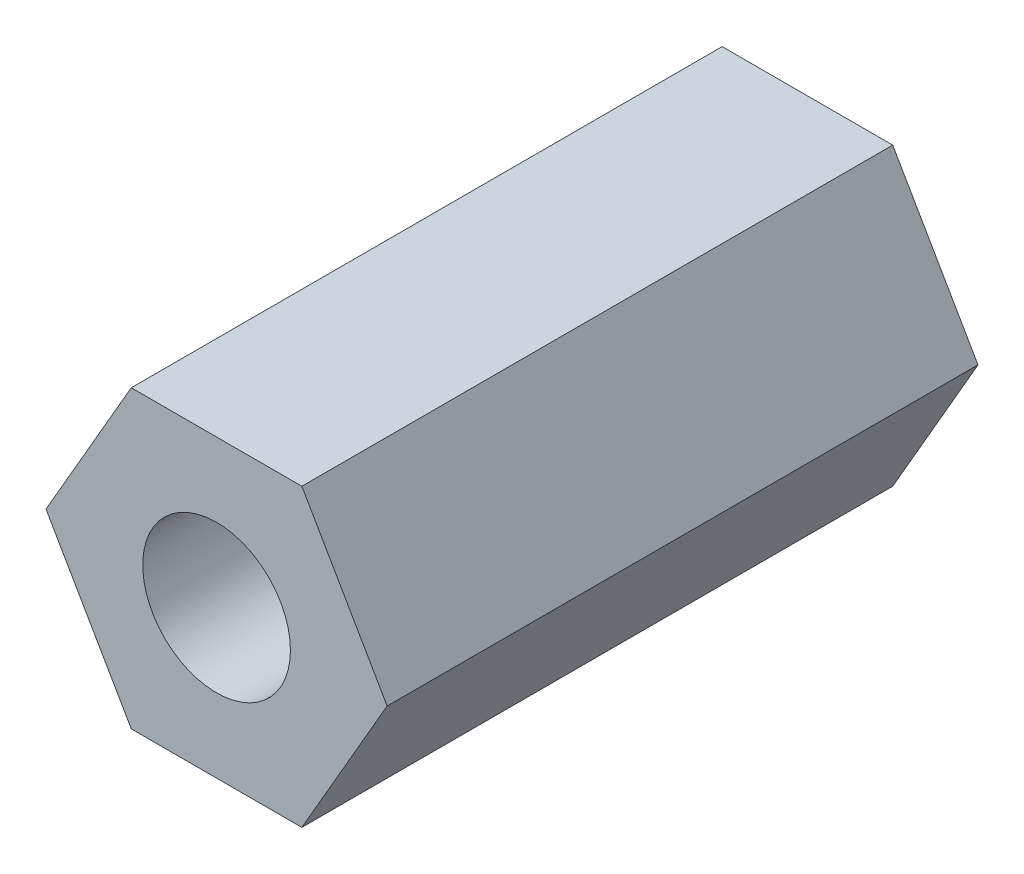
SolidWorks part; units mm, degrees
ref_plane "Front Plane" through (0, 0, 0) normal (0, 0, 1) x (1, 0, 0)
ref_plane "Top Plane" through (0, 0, 0) normal (0, 1, 0) x (1, 0, 0)
ref_plane "Right Plane" through (0, 0, 0) normal (1, 0, 0) x (0, 0, -1)
sketch "Sketch1" plane through (0, 0, 0) normal (0, 0, 1) x (1, 0, 0)
  line L1 (7.3323, 0) -> (3.6662, 6.35)
  line L2 (3.6662, 6.35) -> (-3.6662, 6.35)
  line L3 (-3.6662, 6.35) -> (-7.3323, 0)
  line L4 (-7.3323, 0) -> (-3.6662, -6.35)
  line L5 (-3.6662, -6.35) -> (3.6662, -6.35)
  line L6 (3.6662, -6.35) -> (7.3323, 0)
  circle A0 centre (0, 0) radius 6.35 construction
  circle A1 centre (0, 0) radius 3.175
  dimension "D1" = 12.7
  dimension "D2" = 6.35
extrude "Boss-Extrude1" add sketch "Sketch1" along normal blind 25.4
